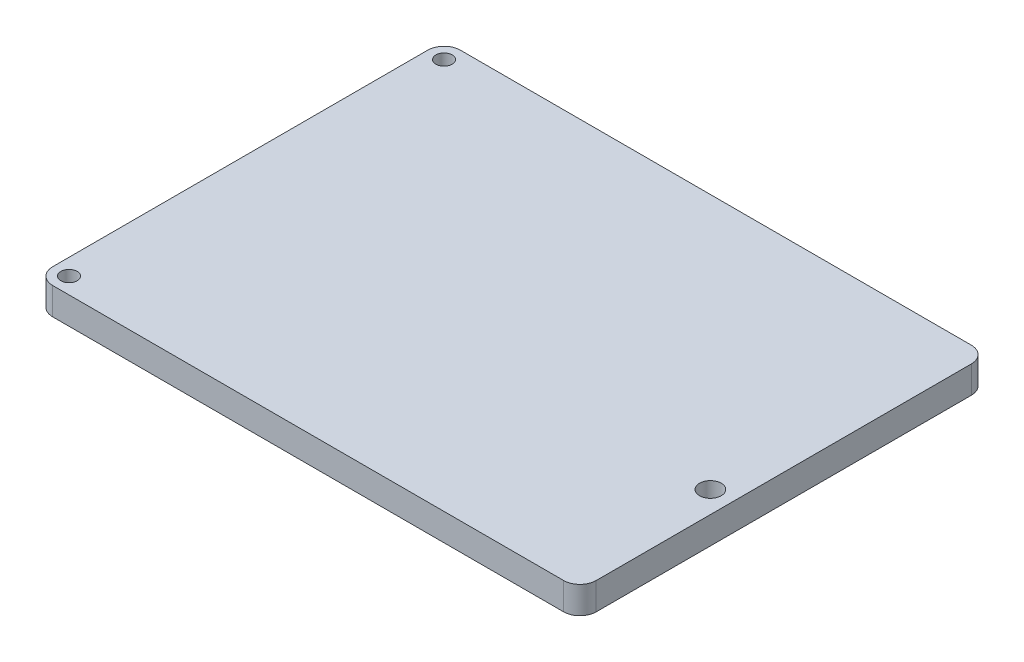
SolidWorks part; units mm, degrees
ref_plane "前视基准面" through (0, 0, 0) normal (0, 0, 1) x (1, 0, 0)
ref_plane "上视基准面" through (0, 0, 0) normal (0, 1, 0) x (1, 0, 0)
ref_plane "右视基准面" through (0, 0, 0) normal (1, 0, 0) x (0, 0, -1)
other "Configuration Table"
sketch "草图1" plane through (0, 0, 0) normal (0, 1, 0) x (1, 0, 0)
  line L0 (96, 0) -> (96, -75) construction
  line L1 (3, 0) -> (97, 0)
  line L2 (0, -3) -> (0, -72)
  line L3 (3, -75) -> (97, -75)
  line L4 (100, -3) -> (100, -72)
  line L5 (0, -47) -> (100, -47) construction
  arc A0 (97, -75) -> (100, -72) centre (97, -72) ccw
  arc A1 (0, -72) -> (3, -75) centre (3, -72) ccw
  arc A2 (97, 0) -> (100, -3) centre (97, -3) cw
  arc A3 (3, 0) -> (0, -3) centre (3, -3) ccw
  circle A4 centre (3, -3) radius 1.5
  circle A5 centre (3, -72) radius 1.5
  circle A6 centre (96, -47) radius 2
  point P9 (0, -75)
  point P12 (100, 0)
  point P15 (0, 0)
  dimension "D3" = 3
  dimension "D4" = 3
  dimension "D5" = 3
  dimension "D8" = 4
  dimension "D1" = 100
  dimension "D2" = 75
  dimension "D6" = 4
  dimension "D7" = 47
extrude "凸台-拉伸1" add sketch "草图1" along normal blind 5
sketch "草图2" plane through (0, 5, 0) normal (0, 1, 0) x (1, 0, 0)
  text T0 "核心板STM32F407和STM32H750"
